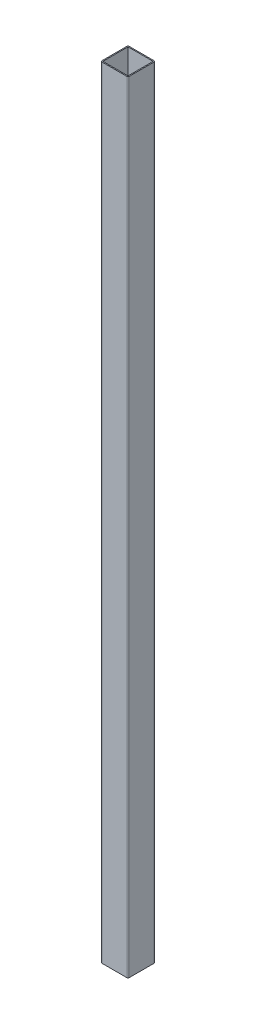
SolidWorks part; units mm, degrees
material "Простая углеродистая сталь"
ref_plane "Спереди" through (0, 0, 0) normal (0, 0, 1) x (1, 0, 0)
ref_plane "Сверху" through (0, 0, 0) normal (0, 1, 0) x (1, 0, 0)
ref_plane "Справа" through (0, 0, 0) normal (1, 0, 0) x (0, 0, -1)
sketch "Эскиз1" plane through (0, 0, 0) normal (0, 0, 1) x (1, 0, 0)
  line L0 (0, 0) -> (0, -4593)
  dimension "D1" = 4593
other "Квадратная труба гост 8639-82 150 X 150 X 7.0(1)"
ref_plane "Плоскость1" through (0, 0, 0) normal (0, -1, 0) x (1, 0, 0)
sketch "Sketch1" plane through (0, 0, 0) normal (0, -1, 0) x (1, 0, 0)
  line L0 (-73.999, -74) -> (73.999, -74)
  line L1 (-74, -73.999) -> (-74, 73.999)
  line L2 (73.999, 74) -> (-73.999, 74)
  line L3 (74, 73.999) -> (74, -73.999)
  line L4 (-73.999, -80) -> (73.999, -80)
  line L5 (-80, -73.999) -> (-80, 73.999)
  line L6 (73.999, 80) -> (-73.999, 80)
  line L7 (80, 73.999) -> (80, -73.999)
  arc A0 (80, 73.999) -> (73.999, 80) centre (73.999, 73.999) ccw
  arc A1 (73.999, -80) -> (80, -73.999) centre (73.999, -73.999) ccw
  arc A2 (-80, -73.999) -> (-73.999, -80) centre (-73.999, -73.999) ccw
  arc A3 (-73.999, 80) -> (-80, 73.999) centre (-73.999, 73.999) ccw
  arc A4 (-73.999, 74) -> (-74, 73.999) centre (-73.999, 73.999) ccw
  arc A5 (74, 73.999) -> (73.999, 74) centre (73.999, 73.999) ccw
  arc A6 (73.999, -74) -> (74, -73.999) centre (73.999, -73.999) ccw
  arc A7 (-74, -73.999) -> (-73.999, -74) centre (-73.999, -73.999) ccw
  point P0 (-80, 0)
  point P1 (80, 0)
  point P2 (0, 80)
  point P3 (0, -80)
  point P4 (0, 0)
  point P5 (-80, -80)
  point P6 (80, -80)
  point P7 (80, 80)
  point P8 (-80, 80)
  point P33 (0, 0)
  dimension "D1" = 6.001
  dimension "Thickness" = 6
  dimension "V_leg" = 160
sketch "Эскиз3" plane through (0, 0, 80) normal (0, 0, 1) x (1, 0, 0)
  line L0 (-80, 0) -> (80, -20)
  line L1 (80, -4593) -> (80, 0) construction
  line L2 (80, -20) -> (80, 0)
  line L3 (80, 0) -> (-80, 0)
  dimension "D1" = 20
extrude "Вырез-Вытянуть1" [suppressed] cut sketch "Эскиз3" against normal up to vertex
equation "\"D1@Sketch1\" = \"Thickness@Sketch1\"+0.001"
